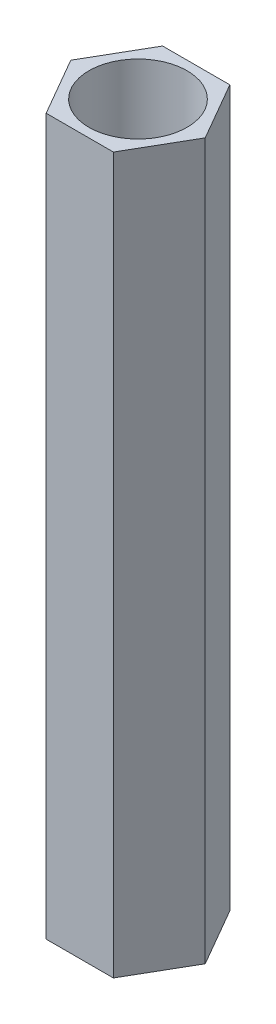
SolidWorks part; units mm, degrees
ref_plane "Alzado" through (0, 0, 0) normal (0, 0, 1) x (1, 0, 0)
ref_plane "Planta" through (0, 0, 0) normal (0, 1, 0) x (1, 0, 0)
ref_plane "Vista lateral" through (0, 0, 0) normal (1, 0, 0) x (0, 0, -1)
sketch "Croquis1" plane through (0, 0, 0) normal (0, 1, 0) x (1, 0, 0)
  line L1 (2.5, 0) -> (1.25, 2.1651)
  line L2 (1.25, 2.1651) -> (-1.25, 2.1651)
  line L3 (-1.25, 2.1651) -> (-2.5, 0)
  line L4 (-2.5, 0) -> (-1.25, -2.1651)
  line L5 (-1.25, -2.1651) -> (1.25, -2.1651)
  line L6 (1.25, -2.1651) -> (2.5, 0)
  circle A2 centre (0, 0) radius 2.1651 construction
  circle A3 centre (0, 0) radius 1.825
  dimension "D1" = 5
  dimension "D2" = 3.65
extrude "Saliente-Extruir1" add sketch "Croquis1" along normal blind 26.6
